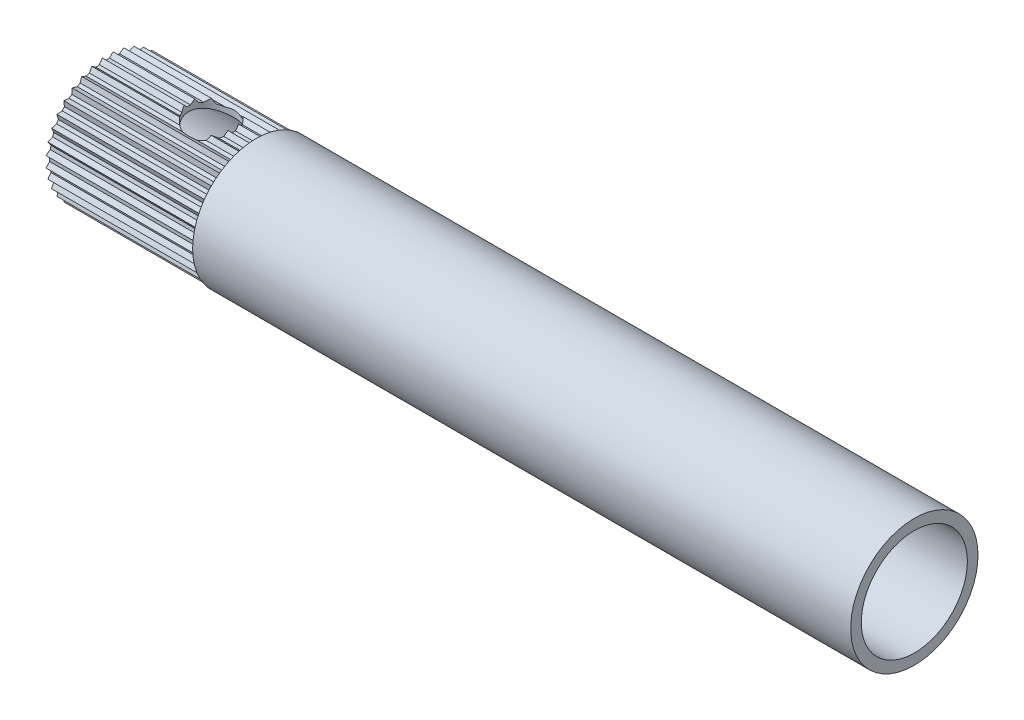
SolidWorks part; units mm, degrees
material "AISI 4130 Steel, normalized at 870C"
ref_plane "X-Y Datum" through (0, 0, 0) normal (0, 0, 1) x (1, 0, 0)
ref_plane "X-Z Datum" through (0, 0, 0) normal (0, 1, 0) x (1, 0, 0)
ref_plane "Y-Z Datum" through (0, 0, 0) normal (1, 0, 0) x (0, 0, -1)
sketch "Sketch1" plane through (0, 0, 0) normal (0, 1, 0) x (1, 0, 0)
  line L0 (139.925, 9.525) -> (139.925, 7.9375)
  line L1 (139.925, 7.9375) -> (19.25, 7.9375)
  line L2 (19.25, 7.9375) -> (19.25, 9.525)
  line L3 (19.25, 9.525) -> (139.925, 9.525)
  line L6 (157.324, 0) -> (-11.2643, 0) construction
  line L7 (19.25, 9.525) -> (19.25, -9.525) construction
  dimension "D1" = 1.5875
revolve "Revolve1" add sketch "Sketch1" angle 360 about L6
sketch "Sketch3" plane through (0, 0, 0) normal (0, 1, 0) x (1, 0, 0)
  circle A0 centre (34.7436, 0) radius 3.3782 construction
  circle A4 centre (34.7436, 0) radius 3.3782
extrude "Cut-Extrude1" cut sketch "Sketch3" against normal through all both and the other way through all
sketch "Sketch4" plane through (0, 0, 0) normal (1, 0, 0) x (0, 0, -1)
  line L0 (-9.2357, 0.808) -> (-8.6817, 0.254)
  line L1 (-8.6817, 0.254) -> (-8.6817, -0.254)
  line L2 (-8.6817, -0.254) -> (-9.2357, -0.808)
  line L3 (-8.6817, 0) -> (0, 0) construction
  line L4 (-8.5939, 1.2574) -> (-9.2357, 0.808)
  line L5 (-8.5057, 1.7577) -> (-8.5939, 1.2574)
  line L6 (-8.9551, 2.3995) -> (-8.5057, 1.7577)
  line L7 (-8.245, 2.7306) -> (-8.9551, 2.3995)
  line L8 (-8.0713, 3.208) -> (-8.245, 2.7306)
  line L9 (-8.4024, 3.9181) -> (-8.0713, 3.208)
  line L10 (-7.6456, 4.1209) -> (-8.4024, 3.9181)
  line L11 (-7.3916, 4.5608) -> (-7.6456, 4.1209)
  line L12 (-7.5944, 5.3176) -> (-7.3916, 4.5608)
  line L13 (-6.8138, 5.3859) -> (-7.5944, 5.3176)
  line L14 (-6.4873, 5.7751) -> (-6.8138, 5.3859)
  line L15 (-6.5556, 6.5556) -> (-6.4873, 5.7751)
  line L16 (-5.7751, 6.4873) -> (-6.5556, 6.5556)
  line L17 (-5.3859, 6.8138) -> (-5.7751, 6.4873)
  line L18 (-5.3176, 7.5944) -> (-5.3859, 6.8138)
  line L19 (-4.5608, 7.3916) -> (-5.3176, 7.5944)
  line L20 (-4.1209, 7.6456) -> (-4.5608, 7.3916)
  line L21 (-3.9181, 8.4024) -> (-4.1209, 7.6456)
  line L22 (-3.208, 8.0713) -> (-3.9181, 8.4024)
  line L23 (-2.7306, 8.245) -> (-3.208, 8.0713)
  line L24 (-2.3995, 8.9551) -> (-2.7306, 8.245)
  line L25 (-1.7577, 8.5057) -> (-2.3995, 8.9551)
  line L26 (-1.2574, 8.5939) -> (-1.7577, 8.5057)
  line L27 (-0.808, 9.2357) -> (-1.2574, 8.5939)
  line L28 (-0.254, 8.6817) -> (-0.808, 9.2357)
  line L29 (0.254, 8.6817) -> (-0.254, 8.6817)
  line L30 (0.808, 9.2357) -> (0.254, 8.6817)
  line L31 (1.2574, 8.5939) -> (0.808, 9.2357)
  line L32 (1.7577, 8.5057) -> (1.2574, 8.5939)
  line L33 (2.3995, 8.9551) -> (1.7577, 8.5057)
  line L34 (2.7306, 8.245) -> (2.3995, 8.9551)
  line L35 (3.208, 8.0713) -> (2.7306, 8.245)
  line L36 (3.9181, 8.4024) -> (3.208, 8.0713)
  line L37 (4.1209, 7.6456) -> (3.9181, 8.4024)
  line L38 (4.5608, 7.3916) -> (4.1209, 7.6456)
  line L39 (5.3176, 7.5944) -> (4.5608, 7.3916)
  line L40 (5.3859, 6.8138) -> (5.3176, 7.5944)
  line L41 (5.7751, 6.4873) -> (5.3859, 6.8138)
  line L42 (6.5556, 6.5556) -> (5.7751, 6.4873)
  line L43 (6.4873, 5.7751) -> (6.5556, 6.5556)
  line L44 (6.8138, 5.3859) -> (6.4873, 5.7751)
  line L45 (7.5944, 5.3176) -> (6.8138, 5.3859)
  line L46 (7.3916, 4.5608) -> (7.5944, 5.3176)
  line L47 (7.6456, 4.1209) -> (7.3916, 4.5608)
  line L48 (8.4024, 3.9181) -> (7.6456, 4.1209)
  line L49 (8.0713, 3.208) -> (8.4024, 3.9181)
  line L50 (8.245, 2.7306) -> (8.0713, 3.208)
  line L51 (8.9551, 2.3995) -> (8.245, 2.7306)
  line L52 (8.5057, 1.7577) -> (8.9551, 2.3995)
  line L53 (8.5939, 1.2574) -> (8.5057, 1.7577)
  line L54 (9.2357, 0.808) -> (8.5939, 1.2574)
  line L55 (8.6817, 0.254) -> (9.2357, 0.808)
  line L56 (8.6817, -0.254) -> (8.6817, 0.254)
  line L57 (9.2357, -0.808) -> (8.6817, -0.254)
  line L58 (8.5939, -1.2574) -> (9.2357, -0.808)
  line L59 (8.5057, -1.7577) -> (8.5939, -1.2574)
  line L60 (8.9551, -2.3995) -> (8.5057, -1.7577)
  line L61 (8.245, -2.7306) -> (8.9551, -2.3995)
  line L62 (8.0713, -3.208) -> (8.245, -2.7306)
  line L63 (8.4024, -3.9181) -> (8.0713, -3.208)
  line L64 (7.6456, -4.1209) -> (8.4024, -3.9181)
  line L65 (7.3916, -4.5608) -> (7.6456, -4.1209)
  line L66 (7.5944, -5.3176) -> (7.3916, -4.5608)
  line L67 (6.8138, -5.3859) -> (7.5944, -5.3176)
  line L68 (6.4873, -5.7751) -> (6.8138, -5.3859)
  line L69 (6.5556, -6.5556) -> (6.4873, -5.7751)
  line L70 (5.7751, -6.4873) -> (6.5556, -6.5556)
  line L71 (5.3859, -6.8138) -> (5.7751, -6.4873)
  line L72 (5.3176, -7.5944) -> (5.3859, -6.8138)
  line L73 (4.5608, -7.3916) -> (5.3176, -7.5944)
  line L74 (4.1209, -7.6456) -> (4.5608, -7.3916)
  line L75 (3.9181, -8.4024) -> (4.1209, -7.6456)
  line L76 (3.208, -8.0713) -> (3.9181, -8.4024)
  line L77 (2.7306, -8.245) -> (3.208, -8.0713)
  line L78 (2.3995, -8.9551) -> (2.7306, -8.245)
  line L79 (1.7577, -8.5057) -> (2.3995, -8.9551)
  line L80 (1.2574, -8.5939) -> (1.7577, -8.5057)
  line L81 (0.808, -9.2357) -> (1.2574, -8.5939)
  line L82 (0.254, -8.6817) -> (0.808, -9.2357)
  line L83 (-0.254, -8.6817) -> (0.254, -8.6817)
  line L84 (-0.808, -9.2357) -> (-0.254, -8.6817)
  line L85 (-1.2574, -8.5939) -> (-0.808, -9.2357)
  line L86 (-1.7577, -8.5057) -> (-1.2574, -8.5939)
  line L87 (-2.3995, -8.9551) -> (-1.7577, -8.5057)
  line L88 (-2.7306, -8.245) -> (-2.3995, -8.9551)
  line L89 (-3.208, -8.0713) -> (-2.7306, -8.245)
  line L90 (-3.9181, -8.4024) -> (-3.208, -8.0713)
  line L91 (-4.1209, -7.6456) -> (-3.9181, -8.4024)
  line L92 (-4.5608, -7.3916) -> (-4.1209, -7.6456)
  line L93 (-5.3176, -7.5944) -> (-4.5608, -7.3916)
  line L94 (-5.3859, -6.8138) -> (-5.3176, -7.5944)
  line L95 (-5.7751, -6.4873) -> (-5.3859, -6.8138)
  line L96 (-6.5556, -6.5556) -> (-5.7751, -6.4873)
  line L97 (-6.4873, -5.7751) -> (-6.5556, -6.5556)
  line L98 (-6.8138, -5.3859) -> (-6.4873, -5.7751)
  line L99 (-7.5944, -5.3176) -> (-6.8138, -5.3859)
  line L100 (-7.3916, -4.5608) -> (-7.5944, -5.3176)
  line L101 (-7.6456, -4.1209) -> (-7.3916, -4.5608)
  line L102 (-8.4024, -3.9181) -> (-7.6456, -4.1209)
  line L103 (-8.0713, -3.208) -> (-8.4024, -3.9181)
  line L104 (-8.245, -2.7306) -> (-8.0713, -3.208)
  line L105 (-8.9551, -2.3995) -> (-8.245, -2.7306)
  line L106 (-8.5057, -1.7577) -> (-8.9551, -2.3995)
  line L107 (-8.5939, -1.2574) -> (-8.5057, -1.7577)
  line L108 (-9.2357, -0.808) -> (-8.5939, -1.2574)
  circle A0 centre (0, 0) radius 8.6854 construction
  circle A1 centre (0, 0) radius 9.271 construction
  circle A2 centre (0, 0) radius 12.7
  point P155 (0, 0)
  dimension "D1" = 18.542
  dimension "D2" = 0.508
  dimension "D3" = 17.3708
  dimension "D6" = 25.4
  dimension "D4" = 135
  dimension "D5" = 1.616
  dimension "D7" = 36
extrude "Cut-Extrude2" cut sketch "Sketch4" along normal blind 22.225 from surface at 19.25 starting at face at (19.25, 0, -7.9375)
